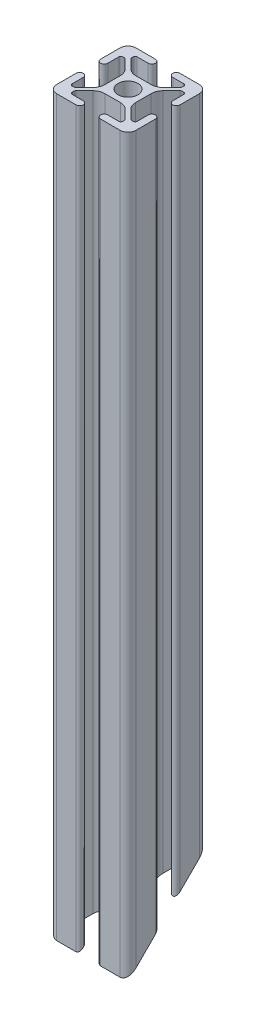
SolidWorks part; units mm, degrees
ref_plane "前视基准面" through (0, 0, 0) normal (0, 0, 1) x (1, 0, 0)
ref_plane "上视基准面" through (0, 0, 0) normal (0, 1, 0) x (1, 0, 0)
ref_plane "右视基准面" through (0, 0, 0) normal (1, 0, 0) x (0, 0, -1)
sketch "草图1" plane through (0, 0, 0) normal (0, 1, 0) x (1, 0, 0)
  line L0 (-1.0428, -10.0859) -> (3.8572, -10.0859)
  line L1 (1.0762, -11.8859) -> (3.8572, -11.8859)
  line L2 (2.8854, -15.3072) -> (0.7226, -13.1443)
  line L3 (2.1786, -16.0141) -> (0.0157, -13.8512)
  line L4 (-3.0428, -12.0859) -> (-3.0428, -16.9859)
  line L5 (-1.2428, -14.2048) -> (-1.2428, -16.9859)
  line L6 (-0.7428, -13.7048) -> (-0.3378, -13.7048)
  line L7 (0.5762, -12.3859) -> (0.5762, -12.7908)
  line L8 (-1.0428, -30.0859) -> (3.8572, -30.0859)
  line L9 (1.0762, -28.2859) -> (3.8572, -28.2859)
  line L10 (2.8854, -24.8645) -> (0.7226, -27.0274)
  line L11 (2.1786, -24.1577) -> (0.0157, -26.3205)
  line L12 (-3.0428, -28.0859) -> (-3.0428, -23.1859)
  line L13 (-1.2428, -25.9669) -> (-1.2428, -23.1859)
  line L14 (-0.7428, -26.4669) -> (-0.3378, -26.4669)
  line L15 (0.5762, -27.7859) -> (0.5762, -27.3809)
  line L16 (14.9572, -10.0859) -> (10.0572, -10.0859)
  line L17 (12.8383, -11.8859) -> (10.0572, -11.8859)
  line L18 (11.029, -15.3072) -> (13.1919, -13.1443)
  line L19 (11.7359, -16.0141) -> (13.8988, -13.8512)
  line L20 (16.9572, -12.0859) -> (16.9572, -16.9859)
  line L21 (15.1572, -14.2048) -> (15.1572, -16.9859)
  line L22 (14.6572, -13.7048) -> (14.2523, -13.7048)
  line L23 (13.3383, -12.3859) -> (13.3383, -12.7908)
  line L24 (14.9572, -30.0859) -> (10.0572, -30.0859)
  line L25 (12.8383, -28.2859) -> (10.0572, -28.2859)
  line L26 (11.029, -24.8645) -> (13.1919, -27.0274)
  line L27 (11.7359, -24.1577) -> (13.8988, -26.3205)
  line L28 (16.9572, -28.0859) -> (16.9572, -23.1859)
  line L29 (15.1572, -25.9669) -> (15.1572, -23.1859)
  line L30 (14.6572, -26.4669) -> (14.2523, -26.4669)
  line L31 (13.3383, -27.7859) -> (13.3383, -27.3809)
  line L32 (5.0068, -16.1859) -> (8.9077, -16.1859)
  line L33 (10.8572, -18.1354) -> (10.8572, -22.0363)
  line L34 (3.0572, -18.1354) -> (3.0572, -22.0363)
  line L35 (5.0068, -23.9859) -> (8.9077, -23.9859)
  circle A0 centre (6.9572, -20.0859) radius 2.5
  arc A1 (2.8854, -15.3072) -> (5.0068, -16.1859) centre (5.0068, -13.1859) ccw
  arc A2 (3.0572, -18.1354) -> (2.1786, -16.0141) centre (0.0572, -18.1354) ccw
  arc A3 (3.8572, -11.8859) -> (3.8572, -10.0859) centre (3.8572, -10.9859) ccw
  arc A4 (0.5762, -12.7908) -> (0.7226, -13.1443) centre (1.0762, -12.7908) ccw
  arc A5 (0.0157, -13.8512) -> (-0.3378, -13.7048) centre (-0.3378, -14.2048) ccw
  arc A6 (-3.0428, -16.9859) -> (-1.2428, -16.9859) centre (-2.1428, -16.9859) ccw
  arc A7 (-1.0428, -10.0859) -> (-3.0428, -12.0859) centre (-1.0428, -12.0859) ccw
  arc A8 (-0.7428, -13.7048) -> (-1.2428, -14.2048) centre (-0.7428, -14.2048) ccw
  arc A9 (1.0762, -11.8859) -> (0.5762, -12.3859) centre (1.0762, -12.3859) ccw
  arc A10 (5.0068, -23.9859) -> (2.8854, -24.8645) centre (5.0068, -26.9859) ccw
  arc A11 (2.1786, -24.1577) -> (3.0572, -22.0363) centre (0.0572, -22.0363) ccw
  arc A12 (3.8572, -30.0859) -> (3.8572, -28.2859) centre (3.8572, -29.1859) ccw
  arc A13 (0.7226, -27.0274) -> (0.5762, -27.3809) centre (1.0762, -27.3809) ccw
  arc A14 (-0.3378, -26.4669) -> (0.0157, -26.3205) centre (-0.3378, -25.9669) ccw
  arc A15 (-1.2428, -23.1859) -> (-3.0428, -23.1859) centre (-2.1428, -23.1859) ccw
  arc A16 (-3.0428, -28.0859) -> (-1.0428, -30.0859) centre (-1.0428, -28.0859) ccw
  arc A17 (-1.2428, -25.9669) -> (-0.7428, -26.4669) centre (-0.7428, -25.9669) ccw
  arc A18 (0.5762, -27.7859) -> (1.0762, -28.2859) centre (1.0762, -27.7859) ccw
  arc A19 (8.9077, -16.1859) -> (11.029, -15.3072) centre (8.9077, -13.1859) ccw
  arc A20 (11.7359, -16.0141) -> (10.8572, -18.1354) centre (13.8572, -18.1354) ccw
  arc A21 (10.0572, -10.0859) -> (10.0572, -11.8859) centre (10.0572, -10.9859) ccw
  arc A22 (13.1919, -13.1443) -> (13.3383, -12.7908) centre (12.8383, -12.7908) ccw
  arc A23 (14.2523, -13.7048) -> (13.8988, -13.8512) centre (14.2523, -14.2048) ccw
  arc A24 (15.1572, -16.9859) -> (16.9572, -16.9859) centre (16.0572, -16.9859) ccw
  arc A25 (16.9572, -12.0859) -> (14.9572, -10.0859) centre (14.9572, -12.0859) ccw
  arc A26 (15.1572, -14.2048) -> (14.6572, -13.7048) centre (14.6572, -14.2048) ccw
  arc A27 (13.3383, -12.3859) -> (12.8383, -11.8859) centre (12.8383, -12.3859) ccw
  arc A28 (11.029, -24.8645) -> (8.9077, -23.9859) centre (8.9077, -26.9859) ccw
  arc A29 (10.8572, -22.0363) -> (11.7359, -24.1577) centre (13.8572, -22.0363) ccw
  arc A30 (10.0572, -28.2859) -> (10.0572, -30.0859) centre (10.0572, -29.1859) ccw
  arc A31 (13.3383, -27.3809) -> (13.1919, -27.0274) centre (12.8383, -27.3809) ccw
  arc A32 (13.8988, -26.3205) -> (14.2523, -26.4669) centre (14.2523, -25.9669) ccw
  arc A33 (16.9572, -23.1859) -> (15.1572, -23.1859) centre (16.0572, -23.1859) ccw
  arc A34 (14.9572, -30.0859) -> (16.9572, -28.0859) centre (14.9572, -28.0859) ccw
  arc A35 (14.6572, -26.4669) -> (15.1572, -25.9669) centre (14.6572, -25.9669) ccw
  arc A36 (12.8383, -28.2859) -> (13.3383, -27.7859) centre (12.8383, -27.7859) ccw
extrude "凸台-拉伸1" add sketch "草图1" along normal blind 185
sketch "草图2" plane through (0, 0, 30.0859) normal (0, 0, 1) x (1, 0, 0)
  line L0 (-3.0428, 0) -> (16.9572, 20)
  line L1 (16.9572, 185) -> (16.9572, 0) construction
  line L2 (5.0068, 0) -> (8.9077, 0) construction
  line L3 (16.9572, 20) -> (16.9572, 0)
  line L4 (16.9572, 0) -> (-3.0428, 0)
  dimension "D1" = 45
sketch "草图3" plane through (16.9572, 0, 0) normal (1, 0, 0) x (0, 0, -1)
  line L0 (-30.0859, 0) -> (-10.0859, 0)
  line L1 (-30.0859, 0) -> (-30.0859, 20) construction
  line L2 (-30.0859, 0) -> (-28.0859, 0) construction
  line L3 (-10.0859, 0) -> (-10.0859, 20)
  line L4 (-10.0859, 185) -> (-10.0859, 0) construction
  line L5 (-10.0859, 20) -> (-30.0859, 0)
extrude "切除-拉伸2" cut sketch "草图3" against normal through all
